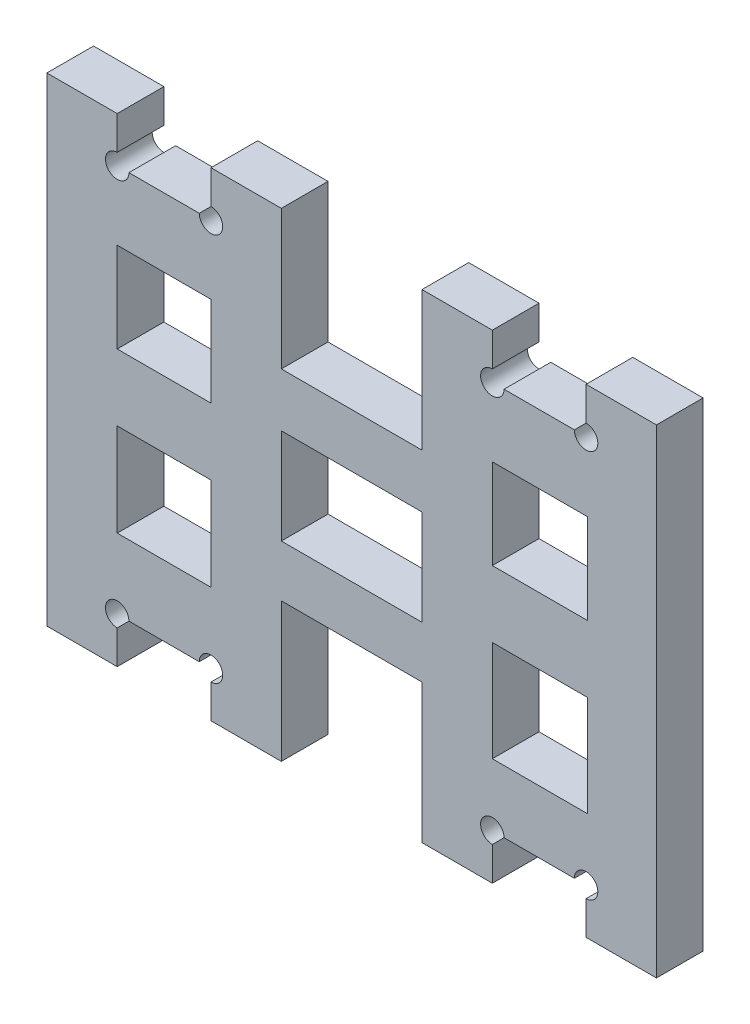
SolidWorks part; units mm, degrees
ref_plane "前视基准面" through (0, 0, 0) normal (0, 0, 1) x (1, 0, 0)
ref_plane "上视基准面" through (0, 0, 0) normal (0, 1, 0) x (1, 0, 0)
ref_plane "右视基准面" through (0, 0, 0) normal (1, 0, 0) x (0, 0, -1)
sketch "草图1" plane through (0, 0, 0) normal (0, 0, 1) x (1, 0, 0)
  line L0 (-10.0437, -6.5677) -> (-10.0437, -10.5458)
  line L1 (-6.0262, -6.5677) -> (-10.0437, -6.5677)
  line L2 (-6.0262, -10.5458) -> (-6.0262, -6.5677)
  line L3 (-10.0437, -10.5458) -> (-6.0262, -10.5458)
  line L4 (10.104, -10.8819) -> (10.104, -6.5677)
  line L5 (6.0262, -10.8819) -> (10.104, -10.8819)
  line L6 (6.0262, -6.5677) -> (6.0262, -10.8819)
  line L7 (10.104, -6.5677) -> (6.0262, -6.5677)
  line L8 (6.0262, 0.1364) -> (6.0262, -3.7141)
  line L9 (10.104, 0.1364) -> (6.0262, 0.1364)
  line L10 (10.104, -3.7141) -> (10.104, 0.1364)
  line L11 (6.0262, -3.7141) -> (10.104, -3.7141)
  line L12 (-3.0131, 5.02) -> (-6.0262, 5.02)
  line L13 (3.0131, 5.02) -> (3.0131, -0.9385)
  line L14 (3.0131, -0.9385) -> (-3.0131, -0.9385)
  line L15 (-3.0131, -0.9385) -> (-3.0131, 5.02)
  line L16 (-10.0437, 5.02) -> (-13.0568, 5.02)
  line L17 (-6.0262, 5.02) -> (-6.0262, 3.5811)
  line L18 (-6.5284, 3.0789) -> (-9.5415, 3.0789)
  line L19 (-10.0437, 3.5811) -> (-10.0437, 5.02)
  line L20 (6.0262, 5.02) -> (3.0131, 5.02)
  line L21 (-13.0568, 5.02) -> (-13.0568, -15.5)
  line L22 (6.0262, -15.5) -> (3.0131, -15.5)
  line L23 (-10.0437, -15.5) -> (-10.0437, -14.0611)
  line L24 (-9.5415, -13.5589) -> (-6.5284, -13.5589)
  line L25 (-6.0262, -14.0611) -> (-6.0262, -15.5)
  line L26 (-3.0131, -15.5) -> (-6.0262, -15.5)
  line L27 (-3.0131, -15.5) -> (-3.0131, -9.5415)
  line L28 (-3.0131, -9.5415) -> (3.0131, -9.5415)
  line L29 (3.0131, -9.5415) -> (3.0131, -15.5)
  line L30 (-10.0437, -15.5) -> (-13.0568, -15.5)
  line L31 (6.0262, -15.5) -> (6.0262, -14.0611)
  line L32 (6.5284, -13.5589) -> (9.5415, -13.5589)
  line L33 (10.0437, -14.0611) -> (10.0437, -15.5)
  line L35 (13.0568, -15.5) -> (13.0568, 5.02)
  line L37 (10.0437, 5.02) -> (10.0437, 3.5811)
  line L38 (9.5415, 3.0789) -> (6.5284, 3.0789)
  line L39 (6.0262, 3.5811) -> (6.0262, 5.02)
  line L40 (-3.0131, -7.324) -> (3.0131, -7.324)
  line L41 (-3.0131, -3.2328) -> (-3.0131, -7.324)
  line L42 (3.0131, -3.2328) -> (-3.0131, -3.2328)
  line L43 (3.0131, -7.324) -> (3.0131, -3.2328)
  line L44 (-10.0437, 0.1364) -> (-10.0437, -3.7141)
  line L45 (-6.0262, 0.1364) -> (-10.0437, 0.1364)
  line L46 (-6.0262, -3.7141) -> (-6.0262, 0.1364)
  line L47 (-10.0437, -3.7141) -> (-6.0262, -3.7141)
  line L49 (13.0568, -15.5) -> (10.0437, -15.5)
  line L51 (13.0568, 5.02) -> (10.0437, 5.02)
  arc A0 (-6.5284, 3.0789) -> (-6.0262, 3.5811) centre (-6.0262, 3.0789) ccw
  arc A1 (-10.0437, 3.5811) -> (-9.5415, 3.0789) centre (-10.0437, 3.0789) ccw
  arc A2 (-9.5415, -13.5589) -> (-10.0437, -14.0611) centre (-10.0437, -13.5589) ccw
  arc A3 (-6.0262, -14.0611) -> (-6.5284, -13.5589) centre (-6.0262, -13.5589) ccw
  arc A4 (6.5284, -13.5589) -> (6.0262, -14.0611) centre (6.0262, -13.5589) ccw
  arc A5 (10.0437, -14.0611) -> (9.5415, -13.5589) centre (10.0437, -13.5589) ccw
  arc A6 (9.5415, 3.0789) -> (10.0437, 3.5811) centre (10.0437, 3.0789) ccw
  arc A7 (6.0262, 3.5811) -> (6.5284, 3.0789) centre (6.0262, 3.0789) ccw
  point P64 (0, 0)
  dimension "D1" = 20.52
extrude "凸台-拉伸1" add sketch "草图1" along normal blind 2
